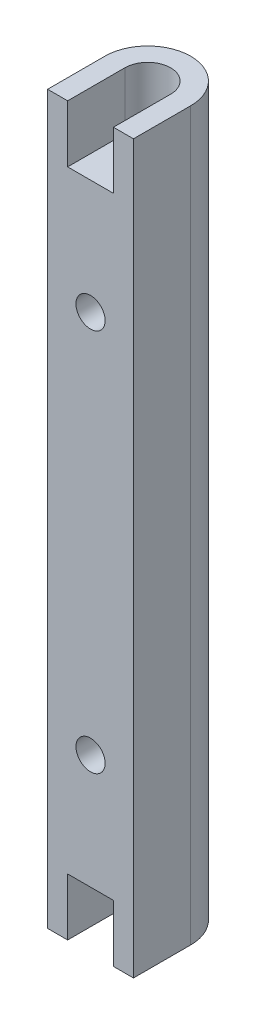
SolidWorks part; units mm, degrees
ref_plane "Front" through (0, 0, 0) normal (0, 0, 1) x (1, 0, 0)
ref_plane "Top" through (0, 0, 0) normal (0, 1, 0) x (1, 0, 0)
ref_plane "Right" through (0, 0, 0) normal (1, 0, 0) x (0, 0, -1)
sketch "Эскиз2" plane through (0, 0, 0) normal (0, 1, 0) x (1, 0, 0)
  line L0 (0, 0) -> (0, -10)
  line L1 (0, -10) -> (15, -10)
  line L2 (15, -10) -> (15, 0)
  arc A0 (0, 0) -> (15, 0) centre (7.5, 0) cw
  dimension "D1" = 0
  dimension "D4" = 15
  dimension "D2" = 10
  dimension "D3" = 7.5
  dimension "D5" = 10
extrude "Бобышка-Вытянуть1" add sketch "Эскиз2" along normal blind 127 contours L1 L2 A0 L0
ref_plane "Плоскость1" through (0, 30, 0) normal (0, -1, 0) x (-1, 0, 0)
sketch "Эскиз4" plane through (0, 30, 0) normal (0, -1, 0) x (-1, 0, 0)
  line L0 (0, -10) -> (-15, -10) construction
  line L1 (-12.5, 0) -> (-12.5, 5.5902)
  line L2 (-10.05, -10) -> (-10.05, 0)
  line L3 (-4.95, -10) -> (-4.95, 0)
  line L4 (-10.05, 0) -> (-12.5, 0)
  line L5 (-4.95, 0) -> (-2.5, 0)
  line L6 (-2.5, 0) -> (-2.5, 5.5902)
  line L8 (-10.05, 0) -> (-4.95, 0) construction
  line L9 (-15, -10) -> (-15, 0) construction
  arc A0 (0, 0) -> (-15, 0) centre (-7.5, 0) ccw construction
  point P13 (-7.5, 0)
  dimension "D1" = 7.5
  dimension "D2" = 10
  dimension "D3" = 5.1
  dimension "D4" = 2.45
  dimension "D5" = 10
sketch "Эскиз6" plane through (0, 0, 10) normal (0, 0, 1) x (1, 0, 0)
  line L0 (-8.25, 30) -> (8.25, 30) construction
  circle A0 centre (7.5, 30) radius 2.55
  dimension "D1" = 5.1
  dimension "D2" = 2.55
extrude "Вырез-Вытянуть1" cut sketch "Эскиз6" against normal blind 14.5 contours A0
ref_plane "Плоскость2" through (0, 0, -4.5) normal (0, 0, 1) x (1, 0, 0)
sketch "Эскиз7" plane through (0, 0, -4.5) normal (0, 0, 1) x (1, 0, 0)
  circle A0 centre (7.5, 30) radius 5
  dimension "D1" = 10
extrude "Вырез-Вытянуть2" cut sketch "Эскиз7" against normal blind 14.5 contours A0
sketch "Эскиз8" plane through (0, 0, 0) normal (0, -1, 0) x (1, 0, 0)
  line L0 (0, 10) -> (15, 10) construction
  line L1 (11.5, 0) -> (11.5, 10)
  line L2 (3.5, 0) -> (3.5, 10)
  line L3 (3.5, 10) -> (11.5, 10)
  arc A0 (3.5, 0) -> (11.5, 0) centre (7.5, 0) ccw
  dimension "D1" = 8
  dimension "D2" = 7.5
  dimension "D3" = 10
extrude "Вырез-Вытянуть3" cut sketch "Эскиз8" against normal blind 10
ref_plane "Плоскость3" through (0, 97, 0) normal (0, 1, 0) x (1, 0, 0)
sketch "Эскиз9" plane through (0, 0, 10) normal (0, 0, 1) x (1, 0, 0)
  line L0 (8.25, 97) -> (-8.25, 97) construction
  line L2 (0, 127) -> (0, 0) construction
  circle A0 centre (7.5, 97) radius 2.55
  dimension "D1" = 5.1
  dimension "D2" = 7.5
extrude "Вырез-Вытянуть4" cut sketch "Эскиз9" against normal blind 14.5 contours A0
sketch "Эскиз10" plane through (0, 0, -4.5) normal (0, 0, 1) x (1, 0, 0)
  circle A0 centre (7.5, 97) radius 5
  point P3 (10, 97)
  point P4 (0, 0)
  point P5 (0, 0)
  dimension "D1" = 10
extrude "Вырез-Вытянуть5" cut sketch "Эскиз10" against normal blind 14.5 contours A0
sketch "Эскиз11" plane through (0, 127, 0) normal (0, 1, 0) x (1, 0, 0)
  line L0 (0, -10) -> (15, -10) construction
  line L1 (11.5, 0) -> (11.5, -10)
  line L2 (11.5, -10) -> (3.5, -10)
  line L3 (3.5, -10) -> (3.5, 0)
  arc A0 (11.5, 0) -> (3.5, 0) centre (7.5, 0) ccw
  dimension "D1" = 8
  dimension "D2" = 7.5
  dimension "D3" = 10
extrude "Вырез-Вытянуть6" cut sketch "Эскиз11" against normal blind 10 contours A0 L3 L2 L1
